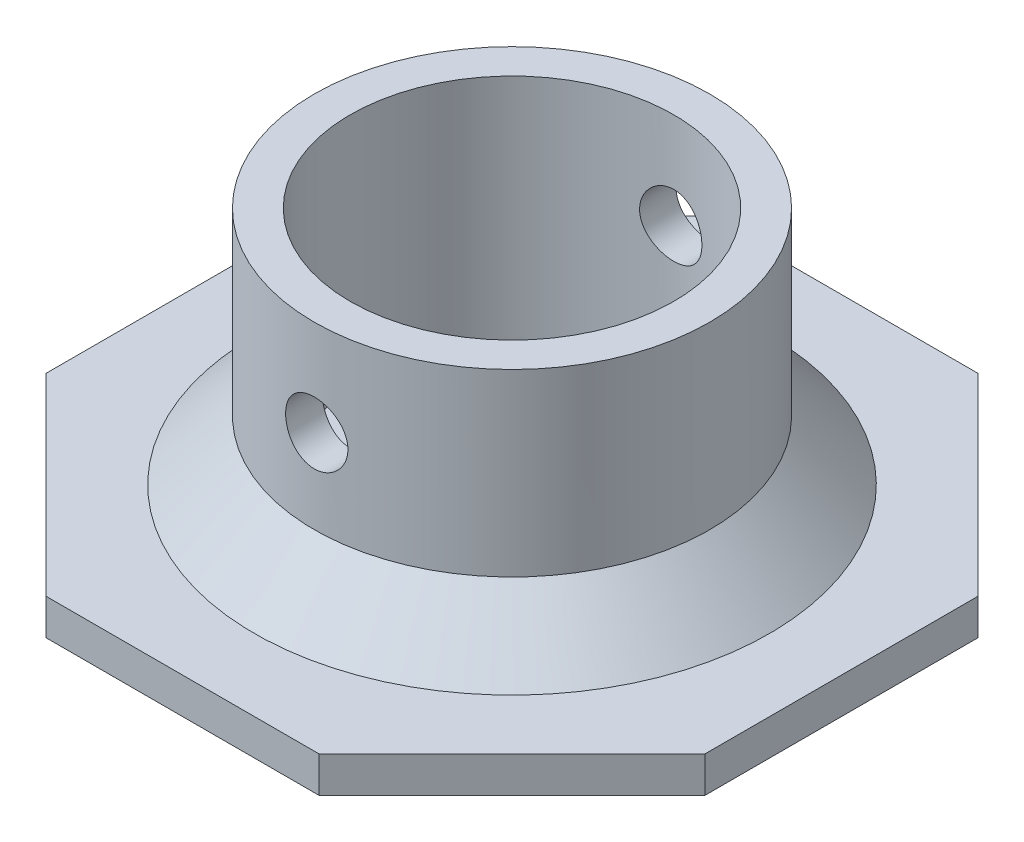
SolidWorks part; units mm, degrees
material "ABS"
ref_plane "Front Plane" through (0, 0, 0) normal (0, 0, 1) x (1, 0, 0)
ref_plane "Top Plane" through (0, 0, 0) normal (0, 1, 0) x (1, 0, 0)
ref_plane "Right Plane" through (0, 0, 0) normal (1, 0, 0) x (0, 0, -1)
sketch "Sketch2" plane through (0, 0, 0) normal (0, 1, 0) x (1, 0, 0)
  line L0 (0, 0) -> (0, 13.5) construction
  line L2 (-11.3909, 27.5) -> (-27.5, 11.3909)
  line L3 (-27.5, 11.3909) -> (-27.5, -11.3909)
  line L4 (-27.5, -11.3909) -> (-11.3909, -27.5)
  line L5 (-11.3909, -27.5) -> (11.3909, -27.5)
  line L6 (11.3909, -27.5) -> (27.5, -11.3909)
  line L7 (27.5, -11.3909) -> (27.5, 11.3909)
  line L8 (27.5, 11.3909) -> (11.3909, 27.5)
  line L9 (11.3909, 27.5) -> (-11.3909, 27.5)
  circle A0 centre (0, 0) radius 13.5 construction
  circle A1 centre (0, 0) radius 27.5 construction
  dimension "D1" = 27
  dimension "D2" = 55
extrude "Boss-Extrude1" add sketch "Sketch2" along normal blind 3
sketch "Sketch4" plane through (0, 3, 0) normal (0, 1, 0) x (1, 0, 0)
  circle A0 centre (0, 0) radius 13.5
  circle A1 centre (0, 0) radius 16.5
  dimension "D1" = 3
extrude "Boss-Extrude2" add sketch "Sketch4" along normal blind 20 contours A1 | A0
sketch "Sketch5" plane through (0, 0, 0) normal (0, 0, 1) x (1, 0, 0)
  line L0 (0, 0) -> (0, 15) construction
  circle A0 centre (0, 15) radius 2.6
  dimension "D2" = 5.2
  dimension "D1" = 15
extrude "Cut-Extrude1" cut sketch "Sketch5" against normal through all and the other way through all
chamfer "Chamfer1" distance 5 angle 45 1 edges at (0, 3, 16.5)
